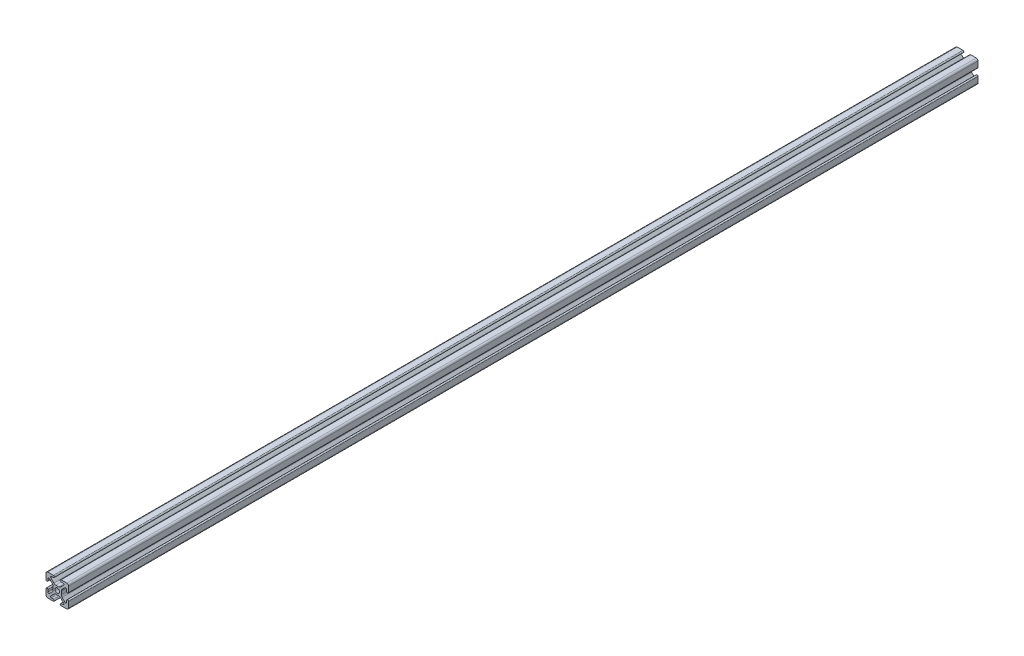
SolidWorks part; units mm, degrees
material "6061 Alloy"
ref_plane "Front Plane" through (0, 0, 0) normal (0, 0, 1) x (1, 0, 0)
ref_plane "Top Plane" through (0, 0, 0) normal (0, 1, 0) x (1, 0, 0)
ref_plane "Right Plane" through (0, 0, 0) normal (1, 0, 0) x (0, 0, -1)
sketch "Sketch1" plane through (0, 0, 0) normal (0, 0, 1) x (1, 0, 0)
  line L0 (-8.6363, 7.1116) -> (-5.4322, 3.9121)
  line L1 (-4.455, 1.5554) -> (-4.455, -1.5554)
  line L2 (-5.4322, -3.9121) -> (-8.6363, -7.1116)
  line L3 (-10.36, -6.3969) -> (-10.36, -4.32)
  line L4 (-12.5, -4.32) -> (-12.5, -8.6518)
  line L5 (-12.5, -8.6518) -> (-12.5, -10.5371)
  line L6 (-10.5371, -12.5) -> (-8.4416, -12.5)
  line L7 (-8.4416, -12.5) -> (-4.3879, -12.5)
  line L8 (-4.3879, -10.36) -> (-6.42, -10.36)
  line L9 (-7.1337, -8.6353) -> (-3.7953, -5.3018)
  line L10 (-1.5554, -4.375) -> (1.5554, -4.375)
  line L11 (10.36, 4.32) -> (10.36, 6.3969)
  line L12 (12.5, 7.9913) -> (12.5, 4.32)
  line L13 (12.5, 10.5371) -> (12.5, 7.9913)
  line L14 (4.32, 12.5) -> (10.5371, 12.5)
  line L16 (6.42, 10.36) -> (4.32, 10.36)
  line L17 (3.7953, 5.3018) -> (7.1337, 8.6353)
  line L18 (7.1337, -8.6353) -> (3.7953, -5.3018)
  line L19 (4.3879, -10.36) -> (6.42, -10.36)
  line L20 (8.4416, -12.5) -> (4.3879, -12.5)
  line L21 (10.5371, -12.5) -> (8.4416, -12.5)
  line L22 (12.5, -8.6518) -> (12.5, -10.5371)
  line L23 (12.5, -4.32) -> (12.5, -8.6518)
  line L24 (10.36, -6.3969) -> (10.36, -4.32)
  line L25 (5.4322, -3.9121) -> (8.6363, -7.1116)
  line L26 (4.455, 1.5554) -> (4.455, -1.5554)
  line L27 (8.6363, 7.1116) -> (5.4322, 3.9121)
  line L28 (1.5554, 4.375) -> (-1.5554, 4.375)
  line L29 (-3.7953, 5.3018) -> (-7.1337, 8.6353)
  line L30 (-6.42, 10.36) -> (-4.32, 10.36)
  line L32 (-4.32, 12.5) -> (-10.5371, 12.5)
  line L33 (-12.5, 10.5371) -> (-12.5, 7.9913)
  line L34 (-12.5, 7.9913) -> (-12.5, 4.32)
  line L35 (-10.36, 4.32) -> (-10.36, 6.3969)
  line L36 (-15.7693, 0) -> (12.5, 0) construction
  line L37 (0, 13.9334) -> (0, -12.3541) construction
  circle A0 centre (0, 0) radius 2.5
  arc A1 (-8.6363, 7.1116) -> (-10.36, 6.3969) centre (-9.35, 6.3969) ccw
  arc A2 (-4.455, 1.5554) -> (-5.4322, 3.9121) centre (-7.7855, 1.5554) ccw
  arc A3 (-5.4322, -3.9121) -> (-4.455, -1.5554) centre (-7.7855, -1.5554) ccw
  arc A4 (-10.36, -6.3969) -> (-8.6363, -7.1116) centre (-9.35, -6.3969) ccw
  arc A5 (-10.36, -4.32) -> (-12.5, -4.32) centre (-11.43, -4.32) ccw
  arc A6 (-12.5, -10.5371) -> (-10.5371, -12.5) centre (-10.5371, -10.5371) ccw
  arc A7 (-4.3879, -12.5) -> (-4.3879, -10.36) centre (-4.3879, -11.43) ccw
  arc A8 (-7.1337, -8.6353) -> (-6.42, -10.36) centre (-6.42, -9.35) ccw
  arc A9 (-1.5554, -4.375) -> (-3.7953, -5.3018) centre (-1.5554, -7.545) ccw
  arc A10 (12.5, 4.32) -> (10.36, 4.32) centre (11.43, 4.32) cw
  arc A11 (10.5371, 12.5) -> (12.5, 10.5371) centre (10.5371, 10.5371) cw
  arc A12 (4.32, 10.36) -> (4.32, 12.5) centre (4.32, 11.43) cw
  arc A13 (6.42, 10.36) -> (7.1337, 8.6353) centre (6.42, 9.35) cw
  arc A14 (3.7953, 5.3018) -> (1.5554, 4.375) centre (1.5554, 7.545) cw
  arc A15 (1.5554, -4.375) -> (3.7953, -5.3018) centre (1.5554, -7.545) cw
  arc A16 (7.1337, -8.6353) -> (6.42, -10.36) centre (6.42, -9.35) cw
  arc A17 (4.3879, -12.5) -> (4.3879, -10.36) centre (4.3879, -11.43) cw
  arc A18 (12.5, -10.5371) -> (10.5371, -12.5) centre (10.5371, -10.5371) cw
  arc A19 (10.36, -4.32) -> (12.5, -4.32) centre (11.43, -4.32) cw
  arc A20 (10.36, -6.3969) -> (8.6363, -7.1116) centre (9.35, -6.3969) cw
  arc A21 (5.4322, -3.9121) -> (4.455, -1.5554) centre (7.7855, -1.5554) cw
  arc A22 (4.455, 1.5554) -> (5.4322, 3.9121) centre (7.7855, 1.5554) cw
  arc A23 (8.6363, 7.1116) -> (10.36, 6.3969) centre (9.35, 6.3969) cw
  arc A24 (-3.7953, 5.3018) -> (-1.5554, 4.375) centre (-1.5554, 7.545) ccw
  arc A25 (-6.42, 10.36) -> (-7.1337, 8.6353) centre (-6.42, 9.35) ccw
  arc A26 (-4.32, 10.36) -> (-4.32, 12.5) centre (-4.32, 11.43) ccw
  arc A27 (-10.5371, 12.5) -> (-12.5, 10.5371) centre (-10.5371, 10.5371) ccw
  arc A28 (-12.5, 4.32) -> (-10.36, 4.32) centre (-11.43, 4.32) ccw
  dimension "D4" = 14.86
  dimension "D5" = 2.14
  dimension "D6" = 6.5
  dimension "D7" = 8.75
  dimension "D8" = 1.01
  dimension "D9" = 3.17
  dimension "D14" = 5
  dimension "D1" = 25
  dimension "D2" = 8.91
  dimension "D3" = 12.5
  dimension "D12" = 2.14
extrude "Extrude1" add sketch "Sketch1" against normal blind 1011.05
